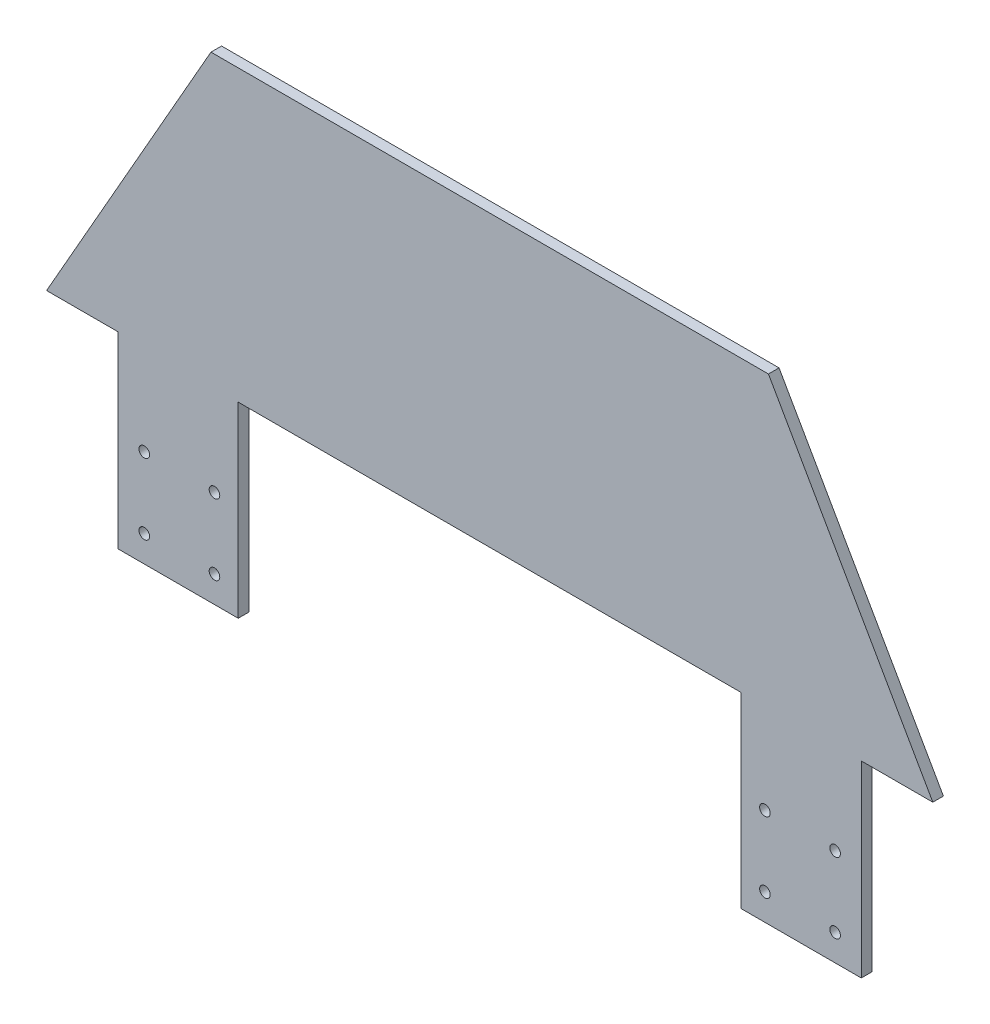
SolidWorks part; units mm, degrees
ref_plane "前视基准面" through (0, 0, 0) normal (0, 0, 1) x (1, 0, 0)
ref_plane "上视基准面" through (0, 0, 0) normal (0, 1, 0) x (1, 0, 0)
ref_plane "右视基准面" through (0, 0, 0) normal (1, 0, 0) x (0, 0, -1)
other "Configuration Table"
sketch "草图1" plane through (0, 0, 0) normal (0, 0, 1) x (1, 0, 0)
  line L1 (-161.4469, -88.1099) -> (161.4469, -88.1099)
  line L2 (-161.4469, -88.1099) -> (-161.4469, 88.1099)
  line L3 (-161.4469, 88.1099) -> (161.4469, 88.1099)
  line L4 (161.4469, -88.1099) -> (161.4469, 88.1099)
  line L5 (-161.4469, -88.1099) -> (161.4469, 88.1099) construction
  line L6 (-161.4469, 88.1099) -> (161.4469, -88.1099) construction
  point P0 (0, 0)
extrude "凸台-拉伸1" add sketch "草图1" along normal blind 3
sketch "草图2" plane through (0, 0, 3) normal (0, 0, 1) x (1, 0, 0)
  line L0 (127.4469, -88.1099) -> (127.4469, -53.1099)
  line L1 (-161.4469, -88.1099) -> (161.4469, -88.1099) construction
  line L2 (127.4469, -53.1099) -> (127.4469, -88.1099) construction
  line L3 (127.4469, -53.1099) -> (-14.9531, -53.1099)
  line L4 (-14.9531, -53.1099) -> (-14.9531, -88.1099)
  line L6 (-14.9531, -88.1099) -> (127.4469, -88.1099)
  line L7 (-48.9531, -88.1099) -> (-48.9531, 88.1099)
  line L9 (161.4469, 88.1099) -> (-161.4469, 88.1099) construction
  line L10 (-48.9531, 88.1099) -> (-161.4469, 88.1099)
  line L11 (-161.4469, 88.1099) -> (-161.4469, -88.1099)
  line L12 (-161.4469, -88.1099) -> (-48.9531, -88.1099)
extrude "切除-拉伸1" cut sketch "草图2" against normal blind 3
sketch "草图3" plane through (0, 0, 3) normal (0, 0, 1) x (1, 0, 0)
  line L0 (56.2469, -53.1099) -> (56.2469, 92.8259) construction
  line L1 (127.4469, -53.1099) -> (-14.9531, -53.1099) construction
  line L2 (146.2469, 46.8901) -> (-33.7531, 46.8901)
  point P7 (56.2469, 46.8901)
  dimension "D1" = 100
sketch "草图4" plane through (0, 0, 3) normal (0, 0, 1) x (1, 0, 0)
  line L0 (127.4469, -88.1099) -> (127.4469, -53.1099) construction
  line L1 (-14.9531, -53.1099) -> (127.4469, -53.1099)
  line L2 (-14.9531, -53.1099) -> (-14.9531, -35.1099)
  line L3 (-14.9531, -35.1099) -> (127.4469, -35.1099)
  line L4 (127.4469, -53.1099) -> (127.4469, -35.1099)
  dimension "D1" = 18
extrude "切除-拉伸2" cut sketch "草图4" against normal through all
sketch "草图6" plane through (0, 0, 0) normal (0, 0, -1) x (-1, 0, 0)
  line L0 (86.9648, -41.2739) -> (3.7512, 56.8399)
sketch "草图8" plane through (0, 0, 0) normal (0, 0, -1) x (-1, 0, 0)
  line L0 (31.8923, 46.9198) -> (-59.5919, 56.989)
sketch "草图9" plane through (0, 0, 3) normal (0, 0, 1) x (1, 0, 0)
  line L0 (-31.8923, 46.9198) -> (161.4469, 46.9198) construction
  line L2 (-86.9648, -41.2739) -> (-3.7512, 56.8399) construction
  line L3 (-86.9648, -41.2739) -> (-3.7512, 56.8399) construction
sketch "草图10" plane through (0, 0, 3) normal (0, 0, 1) x (1, 0, 0)
  line L0 (56.2469, -35.1099) -> (56.2469, 88.1099) construction
  line L1 (127.4469, -35.1099) -> (-14.9531, -35.1099) construction
  line L2 (161.4469, 88.1099) -> (-48.9531, 88.1099) construction
  line L3 (-86.9648, -41.2739) -> (-12.1648, 46.9198)
  line L4 (-86.9648, -41.2739) -> (-3.7512, 56.8399) construction
  line L5 (-200031.8923, 46.9198) -> (200161.4469, 46.9198) construction
  line L6 (-12.1648, 46.9198) -> (124.6585, 46.9198)
  line L7 (56.2469, 46.9198) -> (56.2469, -35.1099)
  line L8 (161.4469, -35.1099) -> (-48.9531, -35.1099)
  line L9 (-48.9531, -88.1099) -> (-48.9531, 88.1099) construction
  line L10 (-48.9531, -35.1099) -> (-48.9531, -41.2739)
  line L11 (-48.9531, -41.2739) -> (-86.9648, -41.2739)
  line L12 (161.4469, -35.1099) -> (161.4469, -41.2739)
  line L13 (199.4585, -41.2739) -> (124.6585, 46.9198)
  line L14 (161.4469, -41.2739) -> (199.4585, -41.2739)
sketch "草图14" plane through (0, 0, 3) normal (0, 0, 1) x (1, 0, 0)
  circle A0 centre (154.0405, -60.6099) radius 1.5
  circle A1 centre (154.0405, -80.6099) radius 1.5
  circle A2 centre (134.1717, -60.6099) radius 1.5
  circle A3 centre (134.1717, -80.6099) radius 1.5
  circle A4 centre (-21.678, -60.6099) radius 1.5
  circle A5 centre (-21.678, -80.6099) radius 1.5
  circle A6 centre (-41.5468, -60.6099) radius 1.5
  circle A7 centre (-41.5468, -80.6099) radius 1.5
extrude "切除-拉伸4" cut sketch "草图14" against normal through all
sketch "草图15" plane through (0, 0, 3) normal (0, 0, 1) x (1, 0, 0)
  line L0 (141.2469, 46.9198) -> (-28.7531, 46.9198)
  line L2 (56.2469, -35.1099) -> (56.2469, 88.1099) construction
  line L3 (-200031.8923, 46.9198) -> (200161.4469, 46.9198) construction
  point P0 (0, 0)
  point P5 (56.2469, 46.9198)
sketch "草图16" plane through (0, 0, 0) normal (0, 0, -1) x (-1, 0, 0)
  line L0 (48.9531, -88.1099) -> (48.9531, 88.1099) construction
  point P0 (48.9531, 3.5441)
sketch "草图18" plane through (0, 0, 0) normal (0, 0, -1) x (-1, 0, 0)
  point P0 (28.7517, 41.8707)
sketch "草图19" plane through (0, 0, 3) normal (0, 0, 1) x (1, 0, 0)
  line L0 (-48.9531, 3.5441) -> (-28.7517, 41.8707) construction
  line L1 (-26.1285, 46.8475) -> (-69.2068, -34.8815)
  line L2 (-69.2068, -34.8815) -> (-48.9531, -34.8815)
  line L3 (-48.9531, -88.1099) -> (-48.9531, 88.1099) construction
  line L4 (56.2469, -35.1099) -> (56.2469, 46.9198)
  line L5 (127.4469, -35.1099) -> (-14.9531, -35.1099) construction
  line L6 (-26.1285, 46.8475) -> (56.2469, 46.9198)
  line L7 (138.6222, 46.8475) -> (56.2469, 46.9198)
  line L8 (181.7005, -34.8815) -> (161.4469, -34.8815)
  line L9 (138.6222, 46.8475) -> (181.7005, -34.8815)
  line L10 (-48.9531, -34.8815) -> (161.4469, -34.8815)
  line M18 (161.4469, -88.1099) -> (161.4469, 88.1099)
  line M20 (-48.9531, 88.1099) -> (-48.9531, -88.1099)
extrude "凸台-拉伸3" add sketch "草图19" against normal blind 3 contours L1 L2 M20 | L9 L8 M18
sketch "草图20" plane through (0, 0, 3) normal (0, 0, 1) x (1, 0, 0)
  line L0 (-48.9531, 3.5441) -> (-48.9531, 88.1099)
  line L1 (-48.9531, 88.1099) -> (161.4469, 88.1099)
  line L2 (161.4469, 88.1099) -> (161.4469, 3.5441)
  line L3 (161.4469, 3.5441) -> (138.6222, 46.8475)
  line L4 (138.6222, 46.8475) -> (-26.1285, 46.8475)
  line L5 (-26.1285, 46.8475) -> (-48.9531, 3.5441)
extrude "切除-拉伸5" cut sketch "草图20" against normal through all
sketch "草图21" plane through (0, 0, 3) normal (0, 0, 1) x (1, 0, 0)
  line L0 (-69.2068, -34.8815) -> (-22.6292, 46.9198)
  line L1 (141.2469, 46.9198) -> (-28.7531, 46.9198) construction
  line L2 (181.7005, -34.8815) -> (135.1222, 46.9198)
  line L3 (-22.6292, 46.9198) -> (-26.1285, 46.8475)
  line L4 (-26.1285, 46.8475) -> (-69.2068, -34.8815)
  line L5 (135.1222, 46.9198) -> (138.6222, 46.8475)
  line L6 (138.6222, 46.8475) -> (181.7005, -34.8815)
  dimension "D1" = 3.5
  dimension "D2" = 3.5
extrude "切除-拉伸6" cut sketch "草图21" against normal through all
